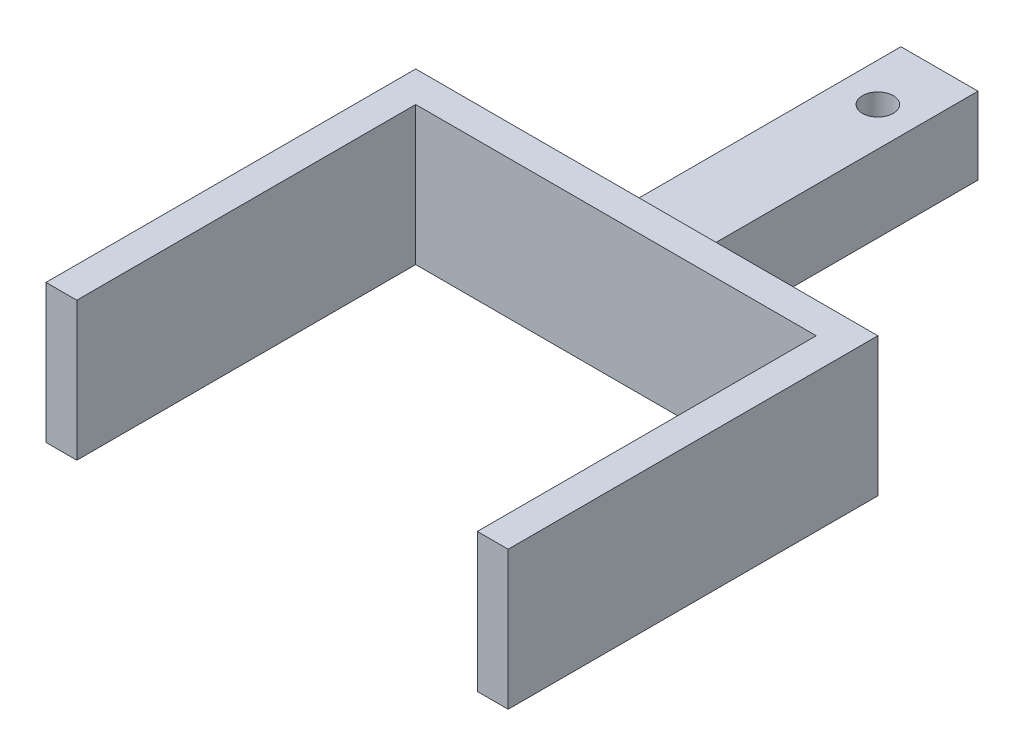
SolidWorks part; units mm, degrees
ref_plane "Front Plane" through (0, 0, 0) normal (0, 0, 1) x (1, 0, 0)
ref_plane "Top Plane" through (0, 0, 0) normal (0, 1, 0) x (1, 0, 0)
ref_plane "Right Plane" through (0, 0, 0) normal (1, 0, 0) x (0, 0, -1)
sketch "Esquisse1" plane through (0, 0, 0) normal (0, 0, 1) x (1, 0, 0)
  line L1 (0, 0) -> (-25, 0)
  line L2 (0, 0) -> (0, -25)
  line L3 (0, -25) -> (-25, -25)
  line L4 (-25, 0) -> (-25, -25)
  line L5 (-12.5, -25) -> (-12.5, 0) construction
  line L6 (0, -12.5) -> (-25, -12.5) construction
  point P112 (-12.5, -12.5)
  dimension "D1" = 25
extrude "Boss.-Extru.1" add sketch "Esquisse1" along normal blind 95
sketch "Esquisse2" plane through (0, 0, 95) normal (0, 0, 1) x (1, 0, 0)
  line L0 (0, 0) -> (-25, 0) construction
  line L1 (52.5, 10) -> (-77.5, 10)
  line L2 (52.5, 10) -> (52.5, -35)
  line L3 (52.5, -35) -> (-77.5, -35)
  line L4 (-77.5, 10) -> (-77.5, -35)
  line L5 (52.5, 10) -> (-77.5, -35) construction
  line L6 (52.5, -35) -> (-77.5, 10) construction
  line L7 (0, -25) -> (0, 0) construction
  point P0 (-12.5, -12.5)
  point P9 (-12.5, 0)
  point P12 (0, -12.5)
  dimension "D1" = 45
  dimension "D2" = 130
extrude "Boss.-Extru.2" add sketch "Esquisse2" along normal blind 10
sketch "Esquisse4" plane through (0, 10, 0) normal (0, 1, 0) x (1, 0, 0)
  line L0 (-12.5, 0) -> (-12.5, -105) construction
  line L1 (-77.5, -95) -> (-87.5, -95)
  line L2 (-77.5, -95) -> (-77.5, -215)
  line L3 (-77.5, -215) -> (-87.5, -215)
  line L4 (-87.5, -95) -> (-87.5, -215)
  line L5 (-82.5, -215) -> (-82.5, -95) construction
  line L6 (-77.5, -155) -> (-87.5, -155) construction
  line L7 (0, 0) -> (-25, 0) construction
  line L8 (52.5, -105) -> (-77.5, -105) construction
  line L9 (52.5, -155) -> (62.5, -155) construction
  line L10 (57.5, -215) -> (57.5, -95) construction
  line L11 (62.5, -95) -> (62.5, -215)
  line L12 (52.5, -215) -> (62.5, -215)
  line L13 (52.5, -95) -> (52.5, -215)
  line L14 (52.5, -95) -> (62.5, -95)
  point P20 (57.5, -155)
  point P40 (-82.5, -155)
  dimension "D1" = 120
  dimension "D2" = 10
extrude "Boss.-Extru.3" add sketch "Esquisse4" against normal up to surface (45 mm away) up to face at (-12.5, -35, 100)
sketch "Esquisse5" plane through (0, 0, 0) normal (0, 1, 0) x (1, 0, 0)
  line L0 (0, -95) -> (0, 0) construction
  line L1 (0, 0) -> (-25, 0) construction
  circle A0 centre (-12.5, -20) radius 5
  dimension "D1" = 10
  dimension "D2" = 12.5
  dimension "D3" = 20
extrude "Enlèv. mat.-Extru.1" cut sketch "Esquisse5" against normal through all
sketch "Esquisse6" plane through (0, -25, 0) normal (0, -1, 0) x (1, 0, 0)
  circle A0 centre (-12.5, 20) radius 9.998
extrude "Enlèv. mat.-Extru.2" cut sketch "Esquisse6" against normal blind 10
